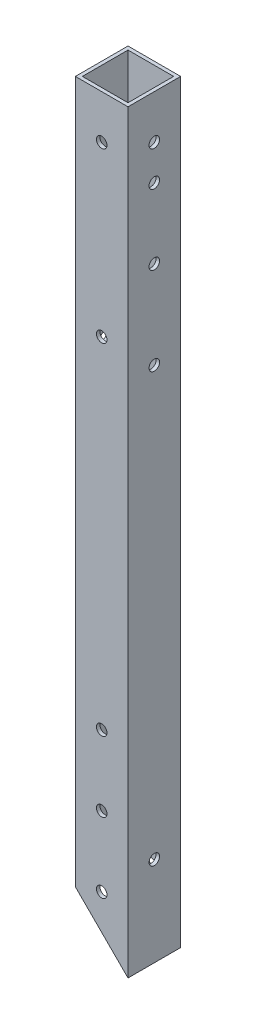
SolidWorks part; units mm, degrees
material "6061-O (SS)"
ref_plane "前视基准面" through (0, 0, 0) normal (0, 0, 1) x (1, 0, 0)
ref_plane "上视基准面" through (0, 0, 0) normal (0, 1, 0) x (1, 0, 0)
ref_plane "右视基准面" through (0, 0, 0) normal (1, 0, 0) x (0, 0, -1)
sketch "草图1" plane through (0, 0, 0) normal (0, 1, 0) x (1, 0, 0)
  line L0 (-6.5, 6.5) -> (6.5, 6.5)
  line L1 (-7.5, -7.5) -> (7.5, -7.5)
  line L2 (-7.5, -7.5) -> (-7.5, 7.5)
  line L3 (-7.5, 7.5) -> (7.5, 7.5)
  line L4 (7.5, -7.5) -> (7.5, 7.5)
  line L5 (-7.5, -7.5) -> (7.5, 7.5) construction
  line L6 (-7.5, 7.5) -> (7.5, -7.5) construction
  line L7 (6.5, -6.5) -> (6.5, 6.5)
  line L8 (-6.5, -6.5) -> (6.5, -6.5)
  line L9 (-6.5, -6.5) -> (-6.5, 6.5)
  point P0 (0, 0)
  dimension "D2" = 15
  dimension "D1" = 1
extrude "凸台-拉伸1" add sketch "草图1" along normal blind 215
sketch "草图2" plane through (0, 0, 7.5) normal (0, 0, 1) x (1, 0, 0)
  line L0 (7.5, 0) -> (-7.5, 0)
  line L1 (-7.5, 0) -> (-7.5, 15)
  line L2 (-7.5, 215) -> (-7.5, 0) construction
  line L3 (-7.5, 15) -> (7.5, 0)
  line L4 (-7.5, 215) -> (7.5, 215) construction
  line L8 (7.5, 215) -> (7.5, 0) construction
  line L9 (0, 7.5) -> (0, 215) construction
  circle A0 centre (0, 37.5) radius 1.5
  circle A1 centre (0, 17.5) radius 1.5
  circle A2 centre (0, 57.5) radius 1.5
  circle A3 centre (0, 202.5) radius 1.5
  circle A4 centre (0, 154.5) radius 1.5
  dimension "D1" = 3
  dimension "D2" = 20
  dimension "D3" = 20
  dimension "D4" = 10
  dimension "D5" = 12.5
  dimension "D6" = 3
  dimension "D7" = 60.5
  dimension "D8" = 3
extrude "切除-拉伸1" cut sketch "草图2" against normal through all
sketch "草图3" plane through (7.5, 0, 0) normal (1, 0, 0) x (0, 0, -1)
  line L0 (0, 215) -> (0, 0) construction
  line L2 (-7.5, 0) -> (7.5, 0) construction
  line L3 (-7.5, 215) -> (7.5, 215) construction
  circle A0 centre (0, 172.5) radius 1.5
  circle A1 centre (0, 192.5) radius 1.5
  circle A2 centre (0, 147.5) radius 1.5
  circle A3 centre (0, 202.5) radius 1.5
  circle A4 centre (0, 25.5) radius 1.5
  dimension "D1" = 12.5
  dimension "D2" = 25
  dimension "D3" = 20
  dimension "D4" = 3
  dimension "D5" = 10
  dimension "D6" = 3
  dimension "D8" = 3
  dimension "D7" = 25.5
extrude "切除-拉伸2" cut sketch "草图3" against normal through all
